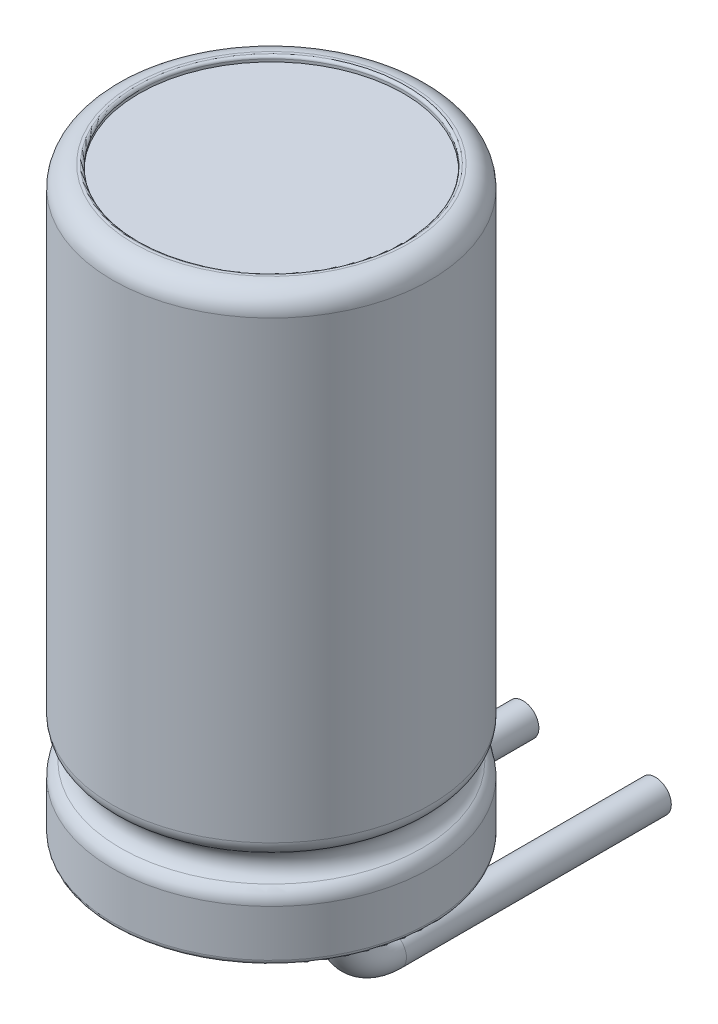
SolidWorks part; units mm, degrees
ref_plane "Front Plane" through (0, 0, 0) normal (0, 0, 1) x (1, 0, 0)
ref_plane "Top Plane" through (0, 0, 0) normal (0, 1, 0) x (1, 0, 0)
ref_plane "Right Plane" through (0, 0, 0) normal (1, 0, 0) x (0, 0, -1)
sketch "Эскиз2" plane through (0, 0, 0) normal (0, 1, 0) x (1, 0, 0)
  circle A0 centre (0, 0) radius 3
  dimension "D1" = 6
extrude "Бобышка-Вытянуть1" add sketch "Эскиз2" along normal blind 11
sketch "Эскиз3" plane through (0, 0, 0) normal (0, -1, 0) x (1, 0, 0)
  circle A0 centre (0, 0) radius 2.5
  dimension "D1" = 5
extrude "Вырез-Вытянуть1" cut sketch "Эскиз3" against normal blind 0.3
sketch "Эскиз4" plane through (0, 0.3, 0) normal (0, -1, 0) x (1, 0, 0)
  line L0 (0, 3.1513) -> (0, -3.4223) construction
  line L1 (-3.3944, 0) -> (3.3545, 0) construction
  circle A0 centre (-1.25, 0) radius 0.3
  dimension "D1" = 0.6
  dimension "D2" = 1.25
ref_plane "Плоскость1" through (-1.25, 0, 0) normal (-1, 0, 0) x (0, 0, 1)
sketch "Эскиз6" plane through (-1.25, 0, 0) normal (-1, 0, 0) x (0, 0, 1)
  line L0 (0, 0.3) -> (0, -0.7)
  line L1 (-0.3, 0.3) -> (0.3, 0.3) construction
  line L2 (-1, -1.7) -> (-6, -1.7)
  arc A0 (-1, -1.7) -> (0, -0.7) centre (-1, -0.7) ccw
  point P8 (0, -1.7)
  dimension "D3" = 1
  dimension "D1" = 2
  dimension "D2" = 6
sweep "По траектории1" add profiles "Эскиз4" path "Эскиз6"
mirror "Зеркальное отражение1" about plane through (0, 0, 0) normal (1, 0, 0) of bodies 103
sketch "Эскиз7" plane through (0, 11, 0) normal (0, 1, 0) x (1, 0, 0)
  circle A0 centre (0, 0) radius 2.5
  dimension "D1" = 5
extrude "Вырез-Вытянуть2" cut sketch "Эскиз7" against normal blind 0.1
sketch "Эскиз9" plane through (0, 0, 0) normal (1, 0, 0) x (0, 0, -1)
  line L0 (-3, 11) -> (-3, 0) construction
  line L1 (-3, 11) -> (-3, 0) construction
  line L2 (-3, 11) -> (-3, 0) construction
  line L3 (0, -2.3692) -> (0, 14.89) construction
  line L4 (-3, 1.8) -> (-3, 1.2)
  arc A0 (-3, 1.8) -> (-3, 1.2) centre (-3, 1.5) cw
  dimension "D2" = 0.3
  dimension "D1" = 1.5
revolve "Вырез-Повернуть1" cut sketch "Эскиз9" angle 360 about L3
fillet "Скругление1" radius 0.1 2 edges at (0, 0, 3) (0, 0, -2.5)
fillet "Скругление2" radius 0.3 2 edges at (0, 1.8, -3) (0, 1.2, -3)
fillet "Скругление3" radius 0.4 1 edges at (0, 11, 3)
fillet "Скругление4" radius 0.05 1 edges at (0, 11, 2.5)
